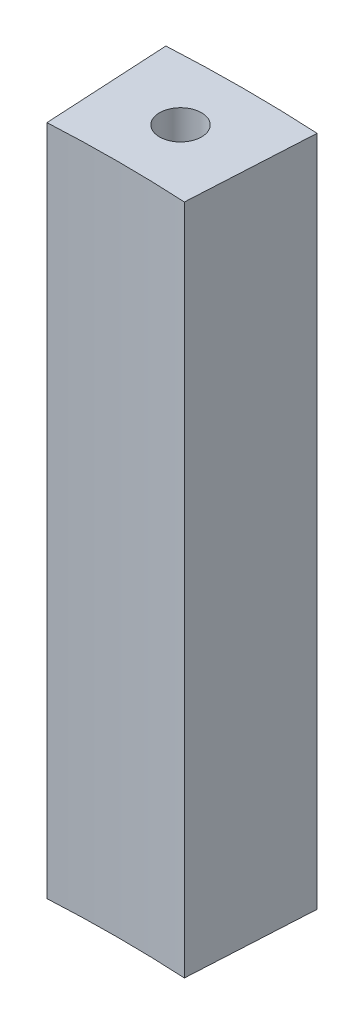
SolidWorks part; units mm, degrees
ref_plane "前视基准面" through (0, 0, 0) normal (0, 0, 1) x (1, 0, 0)
ref_plane "上视基准面" through (0, 0, 0) normal (0, 1, 0) x (1, 0, 0)
ref_plane "右视基准面" through (0, 0, 0) normal (1, 0, 0) x (0, 0, -1)
sketch "草图1" plane through (0, 0, 0) normal (0, 1, 0) x (1, 0, 0)
  line L0 (-8.1818, 149.7767) -> (-9, 164.7544)
  line L1 (8.1818, 149.7767) -> (9, 164.7544)
  line L2 (0, 157.5) -> (0, 0) construction
  arc A0 (9, 164.7544) -> (-9, 164.7544) centre (0, 0) ccw
  arc A1 (8.1818, 149.7767) -> (-8.1818, 149.7767) centre (0, 0) ccw
  circle A2 centre (0, 157.5) radius 2.5
  point P6 (0, 0)
  dimension "D1" = 15
  dimension "D2" = 330
  dimension "D4" = 5
  dimension "D3" = 18
  dimension "D5" = 157.5
extrude "凸台-拉伸1" add sketch "草图1" along normal blind 80
